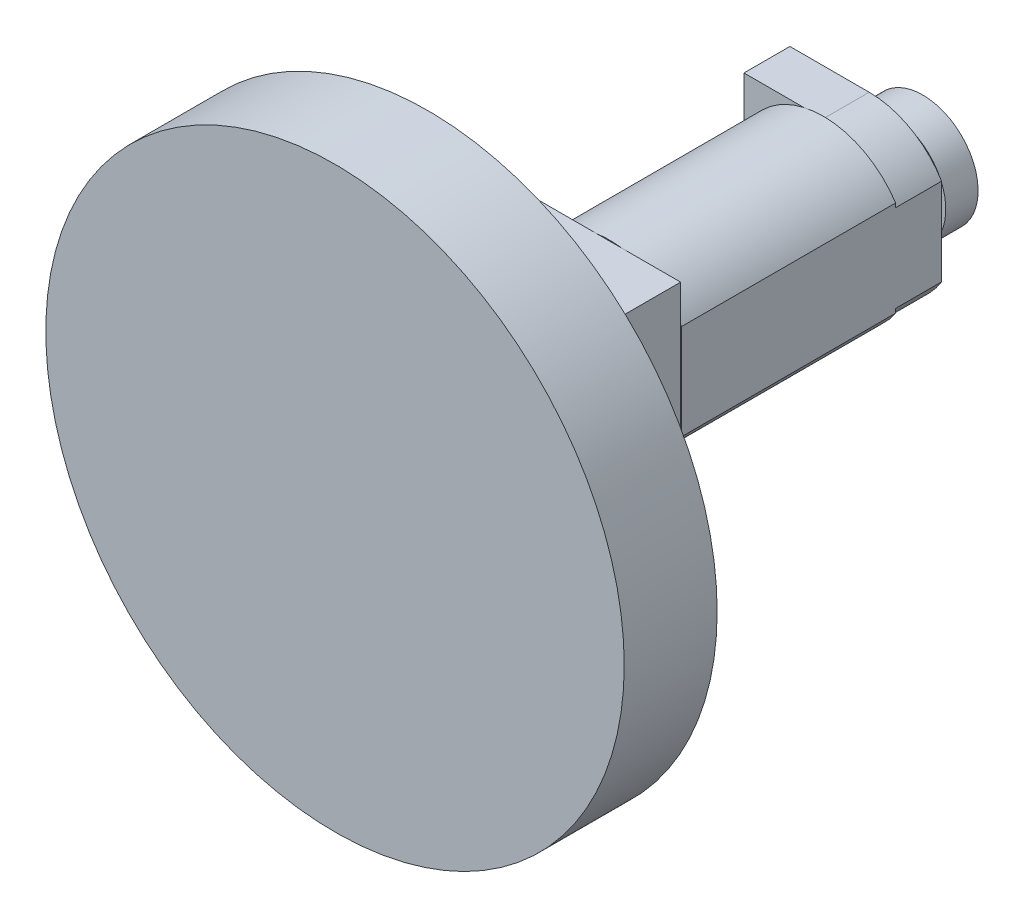
SolidWorks part; units mm, degrees
ref_plane "Front Plane" through (0, 0, 0) normal (0, 0, 1) x (1, 0, 0)
ref_plane "Top Plane" through (0, 0, 0) normal (0, 1, 0) x (1, 0, 0)
ref_plane "Right Plane" through (0, 0, 0) normal (1, 0, 0) x (0, 0, -1)
sketch "Sketch1" plane through (0, 0, 0) normal (0, 0, 1) x (1, 0, 0)
  line L0 (-5.0038, 3.3007) -> (-5.0038, -3.3007)
  line L1 (5.0038, 3.3007) -> (5.0038, -3.3007)
  arc A0 (-5.0038, -3.3007) -> (5.0038, -3.3007) centre (0, 0) ccw
  arc A1 (5.0038, 3.3007) -> (-5.0038, 3.3007) centre (0, 0) ccw
  dimension "D1" = 11.9888
  dimension "D2" = 10.0076
extrude "Boss-Extrude1" add sketch "Sketch1" along normal blind 14.8082
sketch "Sketch2" plane through (0, 0, 14.8082) normal (0, 0, 1) x (1, 0, 0)
  line L1 (-4.9403, 5.9309) -> (4.9403, 5.9309)
  line L2 (-4.9403, 5.9309) -> (-4.9403, -5.9309)
  line L3 (-4.9403, -5.9309) -> (4.9403, -5.9309)
  line L4 (4.9403, 5.9309) -> (4.9403, -5.9309)
  line L5 (-4.9403, 5.9309) -> (4.9403, -5.9309) construction
  line L6 (-4.9403, -5.9309) -> (4.9403, 5.9309) construction
  point P4 (0, 0)
  dimension "D1" = 9.8806
  dimension "D2" = 11.8618
extrude "Boss-Extrude2" add sketch "Sketch2" along normal blind 9.017
sketch "Sketch3" plane through (0, 0, 23.8252) normal (0, 0, 1) x (1, 0, 0)
  line L0 (-1.113, -0.9652) -> (1.113, -0.9652)
  arc A0 (1.113, -0.9652) -> (-1.113, -0.9652) centre (0, 0) ccw
  dimension "D1" = 2.9464
  dimension "D2" = 0.9652
extrude "Boss-Extrude3" add sketch "Sketch3" along normal blind 9.9441
sketch "Sketch4" plane through (0, 0, 33.7693) normal (0, 0, 1) x (1, 0, 0)
  line L0 (-1.113, -0.9652) -> (1.113, -0.9652)
  arc A0 (1.113, -0.9652) -> (-1.113, -0.9652) centre (0, 0) ccw
  circle A1 centre (0, 0) radius 20.0025
  dimension "D1" = 40.005
extrude "Boss-Extrude4" add sketch "Sketch4" against normal blind 6.4262
sketch "Sketch5" plane through (0, 0, 0) normal (0, 0, -1) x (-1, 0, 0)
  line L1 (-5.0038, 3.3007) -> (-5.0038, -3.3007)
  line L2 (0, 5.842) -> (0, -5.842) construction
  line L3 (0, -5.842) -> (5.4864, -5.842)
  line L4 (0, 5.842) -> (5.4864, 5.842)
  line L5 (5.4864, 5.842) -> (5.4864, -5.842)
  line L6 (-5.0038, 3.0151) -> (-5.0038, -3.0151)
  arc A0 (0, 5.842) -> (-5.0038, 3.0151) centre (0, 0) ccw
  arc A1 (-5.0038, -3.0151) -> (0, -5.842) centre (0, 0) ccw
  dimension "D1" = 10.4902
  dimension "D2" = 11.684
extrude "Boss-Extrude5" add sketch "Sketch5" along normal blind 3.175 contours L5 L3 A1 L6 A0 L4
sketch "Sketch7" plane through (0, 0, -3.175) normal (0, 0, -1) x (-1, 0, 0)
  circle A0 centre (0, 0) radius 0.254
  dimension "D1" = 0.508
extrude "Boss-Extrude6" add sketch "Sketch7" along normal blind 1.4732
sketch "Sketch8" plane through (0, 0, -4.6482) normal (0, 0, -1) x (-1, 0, 0)
  circle A0 centre (0, 0) radius 3.8227
  dimension "D1" = 7.6454
extrude "Boss-Extrude7" add sketch "Sketch8" along normal blind 2.2352
